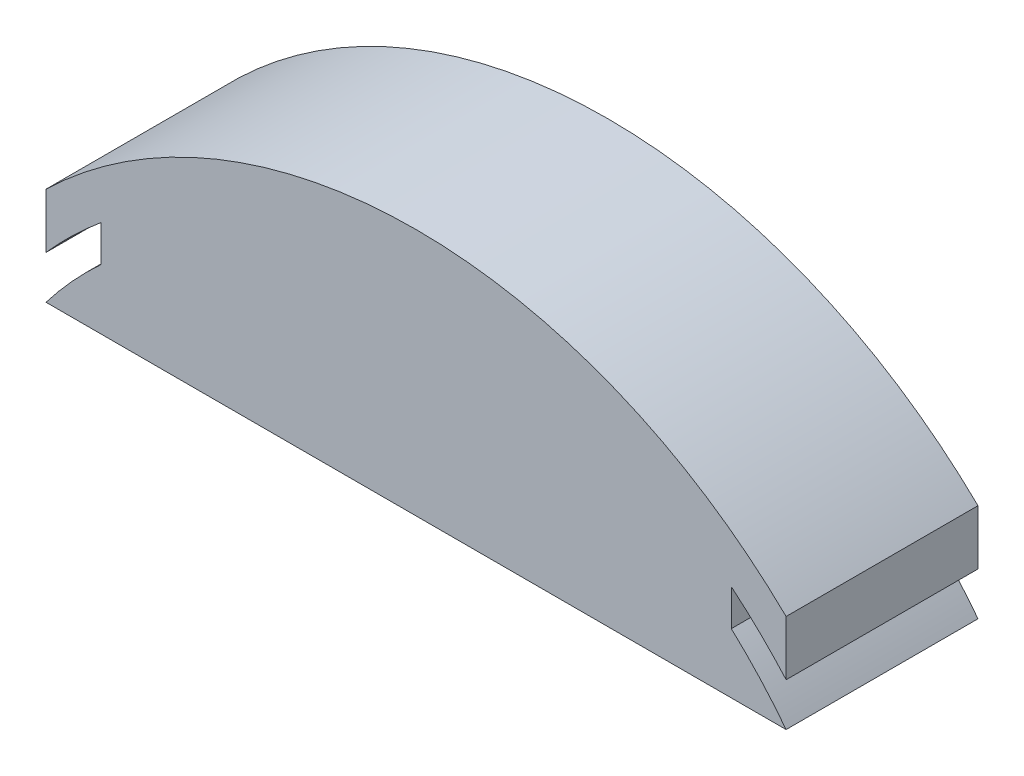
SolidWorks part; units mm, degrees
material "Rubber"
ref_plane "Front Plane" through (0, 0, 0) normal (0, 0, 1) x (1, 0, 0)
ref_plane "Top Plane" through (0, 0, 0) normal (0, 1, 0) x (1, 0, 0)
ref_plane "Right Plane" through (0, 0, 0) normal (1, 0, 0) x (0, 0, -1)
sketch "Sketch1" plane through (0, 0, 0) normal (0, 0, 1) x (1, 0, 0)
  line L0 (0, 0) -> (27, 0)
  line L9 (2, 2.188) -> (2, 3.5154)
  line L10 (25, 2.188) -> (25, 3.5154)
  line L11 (0, 1.5739) -> (0, 3.5739)
  line L12 (27, 1.5739) -> (27, 3.5739)
  arc A0 (0, 0) -> (2, 2.188) centre (13.5, -10.332) cw
  arc A3 (0, 1.5739) -> (2, 3.5154) centre (13.5, -10.332) cw
  arc A4 (0, 3.5739) -> (27, 3.5739) centre (13.5, -10.332) cw
  arc A5 (25, 3.5154) -> (27, 1.5739) centre (13.5, -10.332) cw
  arc A6 (25, 2.188) -> (27, 0) centre (13.5, -10.332) cw
  point P10 (13.5, 0)
  dimension "D1" = 17
  dimension "D6" = 0
  dimension "D8" = 2
  dimension "D5" = 18
  dimension "D2" = 23
  dimension "D3" = 23
  dimension "D4" = 27
  dimension "D7" = 0
  dimension "D10" = 11.5
extrude "Boss-Extrude6" add sketch "Sketch1" along normal blind 7 contours A4 L12 A5 L10 A6 L0 A0 L9 A3 L11
